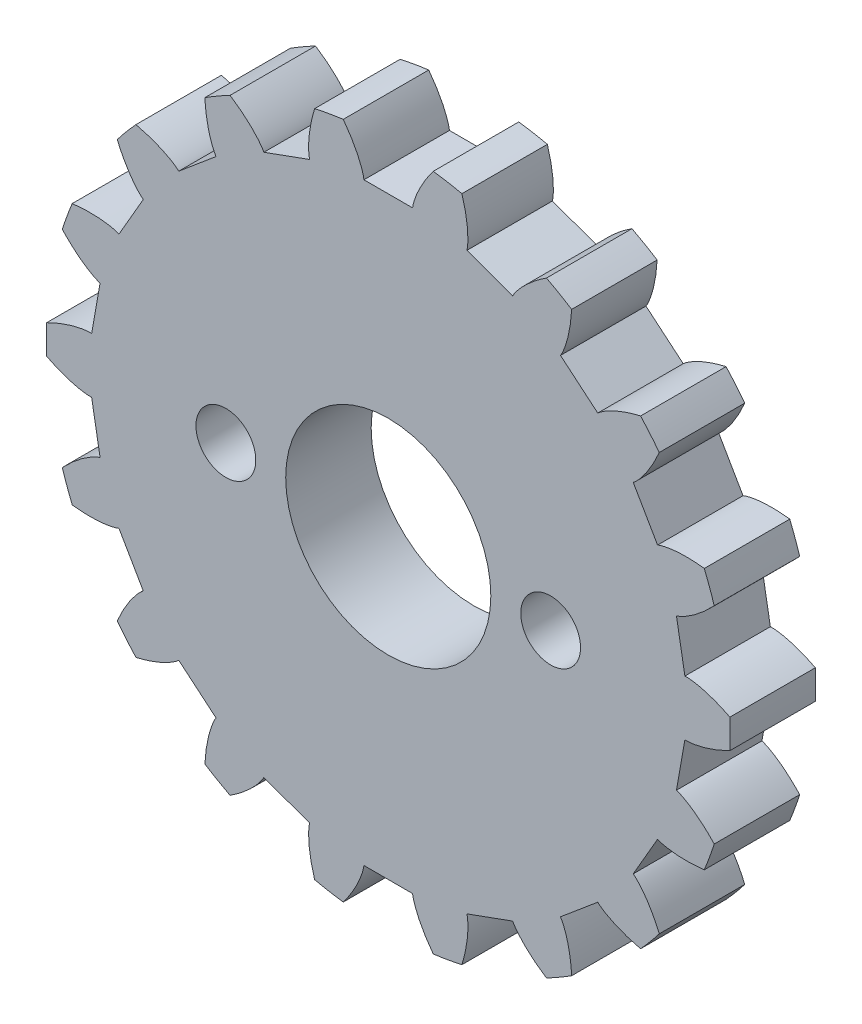
SolidWorks part; units mm, degrees
material "Plain Carbon Steel"
ref_plane "Front Plane" through (0, 0, 0) normal (0, 0, 1) x (1, 0, 0)
ref_plane "Top Plane" through (0, 0, 0) normal (0, 1, 0) x (1, 0, 0)
ref_plane "Right Plane" through (0, 0, 0) normal (1, 0, 0) x (0, 0, -1)
sketch "Sketch1" plane through (0, 0, 0) normal (0, 1, 0) x (1, 0, 0)
  line L0 (0, 0) -> (20, 0)
  line L1 (20, 0) -> (20, -5)
  line L2 (20, -5) -> (0, -5)
  line L3 (0, -5) -> (0, 0)
  line L4 (0, -1) -> (0, -4) construction
  dimension "D1" = 20
  dimension "D2" = 5
revolve "Revolve1" add sketch "Sketch1" angle 360 about L4
sketch "Sketch2" plane through (0, 0, 0) normal (0, 0, 1) x (1, 0, 0)
  spline S0 degree 4 poles (17.3517, 1.6151) (17.3557, 1.6154) (17.3672, 1.6162) (17.3888, 1.617) (17.4242, 1.6176) (17.4695, 1.6171) (17.528, 1.6151) (17.5969, 1.6108) (17.6728, 1.6042) (17.7554, 1.5949) (17.8379, 1.5838) (17.9201, 1.571) (18.002, 1.5568) (18.1012, 1.5377) (18.2201, 1.5122) (18.359, 1.4788) (18.5163, 1.4366) (18.6764, 1.3889) (18.8338, 1.3382) (18.9924, 1.2826) (19.1457, 1.2257) (19.3046, 1.1621) (19.451, 1.1012) (19.6146, 1.0279) (19.7464, 0.9674) (19.9198, 0.8823) (20.022, 0.8305) (20.1414, 0.7681) (20.1943, 0.7394) (20.2269, 0.7218) knots 0 0 0 0 0 0.005377 0.015084 0.028532 0.04661 0.064855 0.092111 0.119476 0.146842 0.174209 0.201575 0.228941 0.256307 0.307035 0.361767 0.4165 0.471232 0.525964 0.580697 0.635429 0.690161 0.744894 0.799626 0.854358 0.909091 0.954545 1 1 1 1 1 construction
  spline S1 degree 4 poles (17.3517, 1.6151) (17.3557, 1.6154) (17.3672, 1.6162) (17.3888, 1.617) (17.4242, 1.6176) (17.4695, 1.6171) (17.528, 1.6151) (17.5969, 1.6108) (17.6728, 1.6042) (17.7554, 1.5949) (17.8379, 1.5838) (17.9201, 1.571) (18.002, 1.5568) (18.1012, 1.5377) (18.2201, 1.5122) (18.359, 1.4788) (18.5163, 1.4366) (18.6764, 1.3889) (18.8338, 1.3382) (18.9924, 1.2826) (19.1457, 1.2257) (19.3046, 1.1621) (19.451, 1.1012) (19.6146, 1.0279) (19.7464, 0.9674) (19.8822, 0.9008) (19.9482, 0.8678) (19.9819, 0.8506) knots 0 0 0 0 0 0.005377 0.015084 0.028532 0.04661 0.064855 0.092111 0.119476 0.146842 0.174209 0.201575 0.228941 0.256307 0.307035 0.361767 0.4165 0.471232 0.525964 0.580697 0.635429 0.690161 0.744894 0.799626 0.854358 0.909091 0.909091 0.909091 0.909091 0.909091
  spline S2 degree 4 poles (16.8576, 4.4169) (16.8615, 4.418) (16.8726, 4.4212) (16.8932, 4.4278) (16.9267, 4.4394) (16.969, 4.4553) (17.0233, 4.4773) (17.0866, 4.5049) (17.1557, 4.537) (17.2301, 4.574) (17.3038, 4.6126) (17.3767, 4.6528) (17.4488, 4.6942) (17.5355, 4.746) (17.6385, 4.8106) (17.7576, 4.8895) (17.891, 4.983) (18.0251, 5.0825) (18.1556, 5.184) (18.2857, 5.2905) (18.4103, 5.3964) (18.5378, 5.5105) (18.6546, 5.6179) (18.7832, 5.7426) (18.8864, 5.8446) (19.0202, 5.9838) (19.0986, 6.0675) (19.1894, 6.167) (19.2293, 6.212) (19.2539, 6.2397) knots 0 0 0 0 0 0.005377 0.015084 0.028532 0.04661 0.064855 0.092111 0.119476 0.146842 0.174209 0.201575 0.228941 0.256307 0.307035 0.361767 0.4165 0.471232 0.525964 0.580697 0.635429 0.690161 0.744894 0.799626 0.854358 0.909091 0.954545 1 1 1 1 1 construction
  spline S3 degree 4 poles (16.8576, 4.4169) (16.8615, 4.418) (16.8726, 4.4212) (16.8932, 4.4278) (16.9267, 4.4394) (16.969, 4.4553) (17.0233, 4.4773) (17.0866, 4.5049) (17.1557, 4.537) (17.2301, 4.574) (17.3038, 4.6126) (17.3767, 4.6528) (17.4488, 4.6942) (17.5355, 4.746) (17.6385, 4.8106) (17.7576, 4.8895) (17.891, 4.983) (18.0251, 5.0825) (18.1556, 5.184) (18.2857, 5.2905) (18.4103, 5.3964) (18.5378, 5.5105) (18.6546, 5.6179) (18.7832, 5.7426) (18.8864, 5.8446) (18.9912, 5.9536) (19.042, 6.0073) (19.0678, 6.0349) knots 0 0 0 0 0 0.005377 0.015084 0.028532 0.04661 0.064855 0.092111 0.119476 0.146842 0.174209 0.201575 0.228941 0.256307 0.307035 0.361767 0.4165 0.471232 0.525964 0.580697 0.635429 0.690161 0.744894 0.799626 0.854358 0.909091 0.909091 0.909091 0.909091 0.909091
  spline S4 degree 4 poles (16.8078, 4.6992) (16.8113, 4.6799) (16.8178, 4.6426) (16.8266, 4.5926) (16.8517, 4.4506) (16.863, 4.3861) (16.8959, 4.1997) (16.9146, 4.094) (16.9415, 3.9411) (16.963, 3.8194) (16.9871, 3.6823) (17.0094, 3.5559) (17.0323, 3.4264) (17.0544, 3.3008) (17.0764, 3.176) (17.0989, 3.0484) (17.1207, 2.9247) (17.1435, 2.7955) (17.1664, 2.6655) (17.1893, 2.5358) (17.2129, 2.4019) (17.2401, 2.2479) (17.2645, 2.1093) (17.295, 1.9363) (17.3155, 1.8203) (17.3466, 1.6437) (17.3594, 1.571) (17.3862, 1.4191) (17.3934, 1.3781) (17.4014, 1.3327) knots 0 0 0 0 0 0.019578 0.039157 0.083333 0.119463 0.163605 0.204742 0.241372 0.282891 0.319568 0.360777 0.395976 0.434538 0.470381 0.508585 0.547934 0.58206 0.623197 0.664835 0.699462 0.745822 0.798764 0.843454 0.882898 0.916667 0.958333 1 1 1 1 1 construction
  spline S5 degree 4 poles (16.8576, 4.4169) (16.8621, 4.3916) (16.8718, 4.3364) (16.8959, 4.1997) (16.9146, 4.094) (16.9415, 3.9411) (16.963, 3.8194) (16.9871, 3.6823) (17.0094, 3.5559) (17.0323, 3.4264) (17.0544, 3.3008) (17.0764, 3.176) (17.0989, 3.0484) (17.1207, 2.9247) (17.1435, 2.7955) (17.1664, 2.6655) (17.1893, 2.5358) (17.2129, 2.4019) (17.2401, 2.2479) (17.2645, 2.1093) (17.295, 1.9363) (17.3155, 1.8203) (17.3385, 1.6898) (17.3475, 1.6387) (17.3517, 1.6151) knots 0.083333 0.083333 0.083333 0.083333 0.083333 0.119463 0.163605 0.204742 0.241372 0.282891 0.319568 0.360777 0.395976 0.434538 0.470381 0.508585 0.547934 0.58206 0.623197 0.664835 0.699462 0.745822 0.798764 0.843454 0.882898 0.916667 0.916667 0.916667 0.916667 0.916667
  spline S6 degree 4 poles (15.9826, 0.6804) (16.2416, 0.6914) (16.7467, 0.7129) (17.6327, 0.7506) (19.6496, 0.8365) (20.7, 0.8812) (23.85, 1.0153) (25.571, 1.0886) (28.17, 1.1992) (30.2279, 1.2868) (32.5626, 1.3862) (34.726, 1.4783) (36.8117, 1.5671) (38.6149, 1.6438) (40.3531, 1.7178) (42.0128, 1.7885) (43.75, 1.8624) (45.5394, 1.9386) (47.2885, 2.0131) (49.0053, 2.0861) (50.6858, 2.1577) (52.4958, 2.2347) (54.0617, 2.3014) (55.8941, 2.3794) (57.1948, 2.4348) (59.3711, 2.5274) (60.1874, 2.5622) (62.142, 2.6454) (62.9087, 2.678) (63.6316, 2.7088) (63.954, 2.7225) knots 0 0 0 0 0 0.020833 0.041667 0.083333 0.130838 0.181419 0.230855 0.273352 0.320856 0.369076 0.415365 0.460365 0.490842 0.521606 0.559333 0.59923 0.635789 0.670272 0.706437 0.740242 0.779733 0.814742 0.847842 0.876173 0.916667 0.945783 0.973695 1 1 1 1 1 construction
  spline S7 degree 4 poles (19.9819, 0.8506) (20.4565, 0.8708) (21.3937, 0.9107) (23.85, 1.0153) (25.571, 1.0886) (28.17, 1.1992) (30.2279, 1.2868) (32.5626, 1.3862) (34.726, 1.4783) (36.8117, 1.5671) (38.6149, 1.6438) (40.3531, 1.7178) (42.0128, 1.7885) (43.75, 1.8624) (45.5394, 1.9386) (47.2885, 2.0131) (49.0053, 2.0861) (50.6858, 2.1577) (52.4958, 2.2347) (54.0617, 2.3014) (55.8941, 2.3794) (57.1948, 2.4348) (58.8875, 2.5068) (59.541, 2.5346) (59.9456, 2.5519) knots 0.083333 0.083333 0.083333 0.083333 0.083333 0.130838 0.181419 0.230855 0.273352 0.320856 0.369076 0.415365 0.460365 0.490842 0.521606 0.559333 0.59923 0.635789 0.670272 0.706437 0.740242 0.779733 0.814742 0.847842 0.876173 0.916667 0.916667 0.916667 0.916667 0.916667
  spline S8 degree 4 poles (59.9925, 0.9582) (59.9903, 1.0719) (59.9858, 1.2917) (59.9809, 1.589) (59.9531, 2.3942) (59.9382, 2.7467) (59.8844, 3.7845) (59.8404, 4.3728) (59.7757, 5.2232) (59.7083, 5.9147) (59.6275, 6.7007) (59.5396, 7.428) (59.441, 8.1887) (59.3335, 8.9279) (59.2167, 9.6768) (59.09, 10.4192) (58.9552, 11.1601) (58.8088, 11.9038) (58.657, 12.6351) (58.4895, 13.3837) (58.3233, 14.0972) (58.1304, 14.8635) (57.9573, 15.5363) (57.7272, 16.3575) (57.5673, 16.9254) (57.2629, 17.919) (57.1563, 18.2553) (56.9071, 19.0215) (56.81, 19.3025) (56.7391, 19.5106) (56.7022, 19.6182) knots 0 0 0 0 0 0.020959 0.041918 0.083333 0.123016 0.162698 0.202381 0.242063 0.281746 0.321429 0.361111 0.400794 0.440476 0.480159 0.519841 0.559524 0.599206 0.638889 0.678571 0.718254 0.757937 0.797619 0.837302 0.876984 0.916667 0.958082 0.979041 1 1 1 1 1 construction
  spline S9 degree 4 poles (59.9456, 2.5519) (59.9389, 2.7089) (59.9243, 3.0145) (59.8844, 3.7845) (59.8404, 4.3728) (59.7757, 5.2232) (59.7083, 5.9147) (59.6275, 6.7007) (59.5396, 7.428) (59.441, 8.1887) (59.3335, 8.9279) (59.2167, 9.6768) (59.09, 10.4192) (58.9552, 11.1601) (58.8088, 11.9038) (58.657, 12.6351) (58.4895, 13.3837) (58.3233, 14.0972) (58.1304, 14.8635) (57.9573, 15.5363) (57.7272, 16.3575) (57.5673, 16.9254) (57.3415, 17.6626) (57.2506, 17.9548) (57.2032, 18.1046) knots 0.083333 0.083333 0.083333 0.083333 0.083333 0.123016 0.162698 0.202381 0.242063 0.281746 0.321429 0.361111 0.400794 0.440476 0.480159 0.519841 0.559524 0.599206 0.638889 0.678571 0.718254 0.757937 0.797619 0.837302 0.876984 0.916667 0.916667 0.916667 0.916667 0.916667
  spline S10 degree 4 poles (61.0255, 19.3144) (60.9277, 19.2834) (60.7398, 19.2239) (60.4589, 19.135) (59.665, 18.8838) (59.0419, 18.6866) (57.4898, 18.1953) (56.7314, 17.9553) (54.8904, 17.3726) (53.7999, 17.0275) (52.2073, 16.5234) (50.7139, 16.0508) (48.8953, 15.4752) (47.1378, 14.9189) (45.1894, 14.3023) (43.4227, 13.7431) (41.5847, 13.1614) (39.695, 12.5633) (37.802, 11.9642) (35.8693, 11.3525) (33.8349, 10.7086) (31.951, 10.1124) (29.7579, 9.4183) (27.7886, 8.795) (25.1148, 7.9487) (23.2554, 7.3602) (19.962, 6.3179) (18.8104, 5.9534) (17.0913, 5.4093) (15.9982, 5.0634) (15.6652, 4.958) (15.3759, 4.8664) (15.2407, 4.8236) knots 0 0 0 0 0 0.007551 0.015102 0.030204 0.057564 0.083333 0.114032 0.147736 0.172793 0.205729 0.238394 0.28756 0.32527 0.363381 0.406275 0.44366 0.48455 0.529948 0.569929 0.615284 0.658128 0.701522 0.750451 0.80619 0.859926 0.916667 0.958333 0.979167 0.989583 1 1 1 1 1 construction
  spline S11 degree 4 poles (57.2032, 18.1046) (56.9105, 18.012) (56.3197, 17.825) (54.8904, 17.3726) (53.7999, 17.0275) (52.2073, 16.5234) (50.7139, 16.0508) (48.8953, 15.4752) (47.1378, 14.9189) (45.1894, 14.3023) (43.4227, 13.7431) (41.5847, 13.1614) (39.695, 12.5633) (37.802, 11.9642) (35.8693, 11.3525) (33.8349, 10.7086) (31.951, 10.1124) (29.7579, 9.4183) (27.7886, 8.795) (25.1148, 7.9487) (23.2554, 7.3602) (20.6221, 6.5268) (19.6087, 6.2061) (19.0678, 6.0349) knots 0.083333 0.083333 0.083333 0.083333 0.083333 0.114032 0.147736 0.172793 0.205729 0.238394 0.28756 0.32527 0.363381 0.406275 0.44366 0.48455 0.529948 0.569929 0.615284 0.658128 0.701522 0.750451 0.80619 0.859926 0.916667 0.916667 0.916667 0.916667 0.916667
extrude "Cut-Extrude2" cut sketch "Sketch2" against normal blind 6 and the other way blind 6
ref_axis "Axis1" through (0, 0, -0.25) along (0, 0, 1)
pattern_circular "CirPattern1" count 18 over 360 about axis through (0, 0, -0.25) along (0, 0, 1) of "Cut-Extrude2"
sketch "Sketch3" plane through (0, 0, 0) normal (0, 0, 1) x (1, 0, 0)
  circle A0 centre (0, 0) radius 6
  circle A1 centre (9.5, 0) radius 1.75
  circle A2 centre (-9.5, 0) radius 1.75
  dimension "D1" = 12
  dimension "D3" = 3.5
  dimension "D5" = 3.5
  dimension "D2" = 9.5
  dimension "D4" = 9.5
extrude "Cut-Extrude4" cut sketch "Sketch3" against normal blind 7 and the other way blind 7
equation "\"TrigProbe\"= cos(60)"
equation "\"SqrProbe\"= sqr(2)"
equation "\"AtnProbe\"= atn(1)"
equation "\"ToothCount\"= 18"
equation "\"DP\"= 12.7"
equation "\"PA\"= 14.5"
equation "\"PArad\"= \"PA\" * 3.14159265358979 / 180"
equation "\"Rb\"= \"ToothCount\" / \"DP\" * cos(\"PA\") / 2"
equation "\"Ra\"= (\"ToothCount\" + 2) / \"DP\" / 2"
equation "\"Tmax\"= sqr(\"Ra\" * \"Ra\" / (\"Rb\" * \"Rb\") - 1)"
equation "\"Delta\"= 3.14159265358979 / (2 * \"ToothCount\") + tan(\"PA\") - \"PArad\""
equation "\"Gamma\"= 2 * 3.14159265358979 / \"ToothCount\""
equation "\"ThetaL\"= atn(\"Tmax\") * 3.14159265358979 / 180 - \"Tmax\" + \"Delta\""
equation "\"ThetaU\"= \"Tmax\" - atn(\"Tmax\") * 3.14159265358979 / 180 - \"Delta\" + \"Gamma\""
equation "\"D1@Sketch1\" = \"Ra\""
equation "\"D1@CirPattern1\" = \"ToothCount\""
